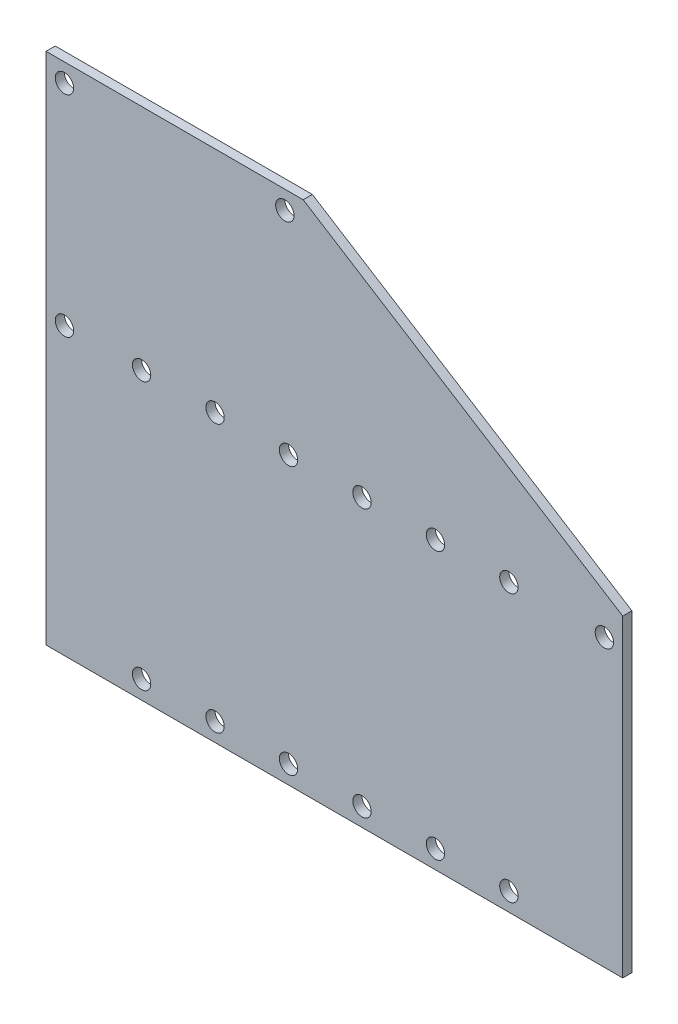
SolidWorks part; units mm, degrees
material "6061-T6 (SS)"
ref_plane "Front Plane" through (0, 0, 0) normal (0, 0, 1) x (1, 0, 0)
ref_plane "Top Plane" through (0, 0, 0) normal (0, 1, 0) x (1, 0, 0)
ref_plane "Right Plane" through (0, 0, 0) normal (1, 0, 0) x (0, 0, -1)
sketch "Sketch1" plane through (0, 0, 0) normal (0, 0, 1) x (1, 0, 0)
  line L1 (-99.695, -88.9) -> (99.695, -88.9)
  line L2 (-99.695, -88.9) -> (-99.695, 88.9)
  line L3 (-99.695, 88.9) -> (99.695, 88.9)
  line L4 (99.695, -88.9) -> (99.695, 88.9)
  line L5 (-99.695, -88.9) -> (99.695, 88.9) construction
  line L6 (-99.695, 88.9) -> (99.695, -88.9) construction
  point P0 (0, 0)
  dimension "D1" = 177.8
  dimension "D2" = 199.39
extrude "Boss-Extrude1" add sketch "Sketch1" along normal blind 3.175 contours L3 L4 L1 L2
sketch "Sketch6" plane through (0, 0, 3.175) normal (0, 0, 1) x (1, 0, 0)
  line L0 (0, 88.9) -> (0, 19.475) construction
  line L1 (-99.695, 88.9) -> (99.695, 88.9) construction
  line L2 (-99.695, 88.9) -> (-10.795, 88.9) construction
  line L11 (99.695, 88.9) -> (99.695, 19.475)
  line L13 (-10.795, 88.9) -> (99.695, 19.475)
  line L14 (0, 19.475) -> (99.695, 19.475) construction
  line L16 (99.695, 88.9) -> (-10.795, 88.9)
  line L18 (99.695, -88.9) -> (99.695, 88.9) construction
  dimension "D1" = 69.425
  dimension "D2" = 88.9
  dimension "D3" = 0
  dimension "D5" = 69.425
extrude "Cut-Extrude4" cut sketch "Sketch6" against normal through all
sketch "Sketch7" plane through (0, 0, 3.175) normal (0, 0, 1) x (1, 0, 0)
  line L0 (-99.695, -88.9) -> (99.695, -88.9) construction
  line L1 (-99.695, -88.9) -> (-99.695, 88.9) construction
  line L2 (99.695, -88.9) -> (99.695, 19.475) construction
  line L3 (-99.695, 88.9) -> (-10.795, 88.9) construction
  line L4 (-66.675, -88.9) -> (-66.675, 9.95) construction
  line L5 (-93.345, 82.55) -> (-17.145, 82.55) construction
  circle A2 centre (-93.345, 82.55) radius 3.175
  circle A3 centre (-93.345, 9.95) radius 3.175
  circle A4 centre (93.345, 9.95) radius 3.175
  circle A5 centre (-66.675, 9.95) radius 3.175
  circle A6 centre (-41.275, 9.95) radius 3.175
  circle A7 centre (-15.875, 9.95) radius 3.175
  circle A8 centre (9.525, 9.95) radius 3.175
  circle A9 centre (34.925, 9.95) radius 3.175
  circle A10 centre (60.325, 9.95) radius 3.175
  circle A11 centre (-17.145, 82.55) radius 3.175
  circle A13 centre (-66.675, -82.55) radius 3.175
  circle A14 centre (-41.275, -82.55) radius 3.175
  circle A15 centre (-15.875, -82.55) radius 3.175
  circle A16 centre (9.525, -82.55) radius 3.175
  circle A17 centre (34.925, -82.55) radius 3.175
  circle A18 centre (60.325, -82.55) radius 3.175
  dimension "D4" = 6
  dimension "D6" = 6.35
  dimension "D9" = 6.35
  dimension "D10" = 6.35
  dimension "D12" = 6
  dimension "D14" = 6.35
  dimension "D16" = 6.35
  dimension "D2" = 6.35
  dimension "D3" = 6.35
  dimension "D5" = 6.35
  dimension "D7" = 6.35
  dimension "D8" = 98.85
  dimension "D11" = 33.02
  dimension "D13" = 98.85
  dimension "3.82923228" = 98.85
  dimension "D15" = 6.35
  dimension "D17" = 6.35
extrude "Cut-Extrude5" cut sketch "Sketch7" against normal through all
sketch "Sketch8" plane through (0, 0, 3.175) normal (0, 0, 1) x (1, 0, 0)
  line L0 (-99.695, -88.9) -> (99.695, -88.9) construction
  line L2 (-77.7875, 19.05) -> (-77.7875, -88.9)
  line L4 (71.4375, 19.05) -> (71.4375, -88.9)
  line L5 (-66.675, -82.55) -> (60.325, -82.55) construction
  line L6 (-66.675, 9.95) -> (60.325, 9.95) construction
  line L7 (-3.175, -82.55) -> (-3.175, -88.9) construction
  line L8 (-80.9625, -88.9) -> (-80.9625, 19.05)
  line L9 (71.4375, 19.05) -> (74.6125, 19.05)
  line L10 (74.6125, 19.05) -> (74.6125, -88.9)
  line L11 (71.4375, -88.9) -> (74.6125, -88.9)
  line L12 (-80.9625, 19.05) -> (-77.7875, 19.05)
  line L13 (-80.9625, -88.9) -> (-77.7875, -88.9)
  line L14 (-77.7875, -34.925) -> (71.4375, -34.925) construction
  point P22 (-3.175, -34.925)
  dimension "D1" = 3.175
  dimension "D2" = 3.175
  dimension "D3" = 149.225
  dimension "D4" = 0
  dimension "D5" = 107.95
extrude "Boss-Extrude2" [suppressed] add sketch "Sketch8" along normal blind 3.175
